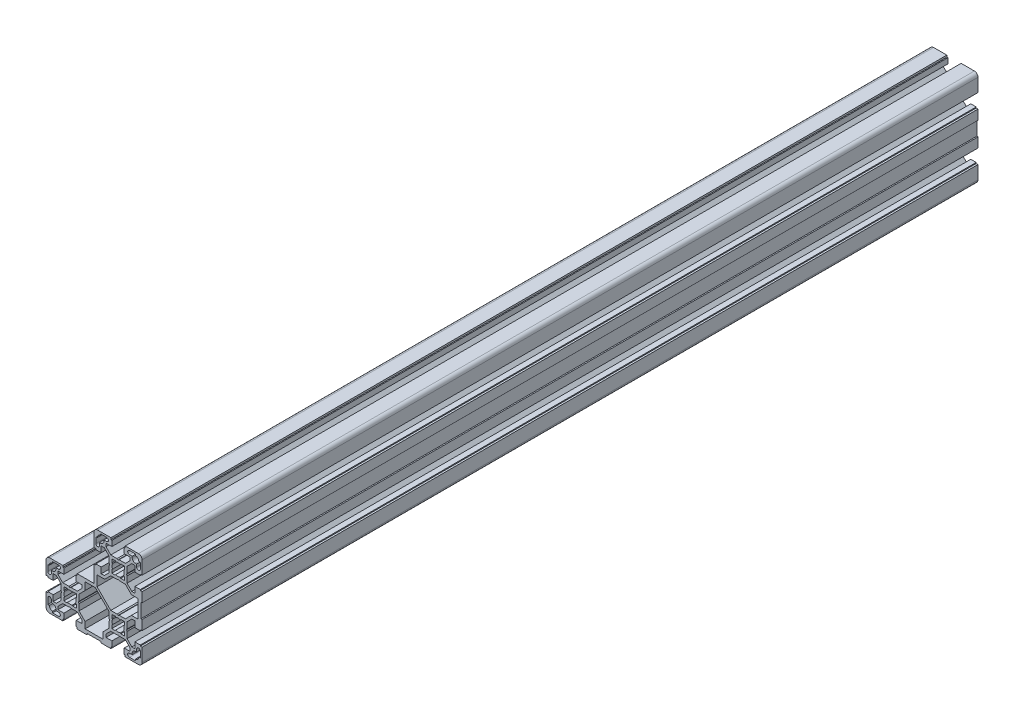
SolidWorks part; units mm, degrees
material "3.1355 (EN-AW 2024)"
ref_plane "Спереди" through (0, 0, 0) normal (0, 0, 1) x (1, 0, 0)
ref_plane "Сверху" through (0, 0, 0) normal (0, 1, 0) x (1, 0, 0)
ref_plane "Справа" through (0, 0, 0) normal (1, 0, 0) x (0, 0, -1)
sketch "Model" plane through (0, 0, 0) normal (0, 0, 1) x (1, 0, 0)
  point P0 (0, 1)
  line B0 (-35.5, 31.7499) -> (-35.5, 29.4999)
  line B1 (-38.5, 29.4999) -> (-38.5, 34.4999)
  line B2 (-38.5, 34.4999) -> (-37.25, 34.4999)
  line B3 (-34.5, 37.2499) -> (-34.5, 38.4999)
  line B4 (-34.5, 38.4999) -> (-29.5, 38.4999)
  line B5 (-29.5, 35.4999) -> (-31.75, 35.4999)
  line B6 (-31.75, 35.4999) -> (-31.75, 34.5077)
  line B7 (-34.5, 31.7499) -> (-35.5, 31.7499)
  line B8 (1.0858, 37.5) -> (12.5001, 26.0857)
  line B9 (12.5001, 26.0857) -> (12.5001, 20.866)
  line B10 (12.5001, 20.866) -> (13.0001, 20)
  line B11 (13.0001, 20) -> (12.5001, 19.1339)
  line B12 (12.5001, 19.1339) -> (12.5001, 13.9142)
  line B13 (12.5001, 13.9142) -> (7.4501, 8.8642)
  line B14 (7.4501, 8.8642) -> (7.4501, 3.5)
  line B15 (7.4501, 3.5) -> (-7.4501, 3.5)
  line B16 (-7.4501, 3.5) -> (-7.4501, 8.8642)
  line B17 (-7.4501, 8.8642) -> (-12.5001, 13.9142)
  line B18 (-12.5001, 13.9142) -> (-12.5001, 19.1339)
  line B19 (-12.5001, 19.1339) -> (-13.0001, 20)
  line B20 (-13.0001, 20) -> (-12.5001, 20.866)
  line B21 (-12.5001, 20.866) -> (-12.5001, 26.0857)
  line B22 (-12.5001, 26.0857) -> (-7.4501, 31.1357)
  line B23 (-7.4501, 31.1357) -> (-7.4501, 37.5)
  line B24 (-7.4501, 37.5) -> (1.0858, 37.5)
  line B25 (25.2, 14.8) -> (22.2603, 14.8)
  line B26 (22.2603, 14.8) -> (21.9932, 15.4144)
  line B27 (18.0068, 15.4144) -> (17.7398, 14.8)
  line B28 (17.7398, 14.8) -> (14.8001, 14.8)
  line B29 (14.8001, 14.8) -> (14.8001, 17.7397)
  line B30 (14.8001, 17.7397) -> (15.4145, 18.0068)
  line B31 (15.4145, 21.9932) -> (14.8001, 22.2602)
  line B32 (14.8001, 22.2602) -> (14.8001, 25.1999)
  line B33 (14.8001, 25.1999) -> (17.7398, 25.1999)
  line B34 (17.7398, 25.1999) -> (18.0068, 24.5855)
  line B35 (21.9932, 24.5855) -> (22.2603, 25.1999)
  line B36 (22.2603, 25.1999) -> (25.2, 25.1999)
  line B37 (25.2, 25.1999) -> (25.2, 22.2602)
  line B38 (25.2, 22.2602) -> (24.5856, 21.9932)
  line B39 (24.5856, 18.0068) -> (25.2, 17.7397)
  line B40 (25.2, 17.7397) -> (25.2, 14.8)
  line B41 (10.5001, 75.5) -> (8.2501, 75.5)
  line B42 (8.2501, 75.5) -> (8.2501, 74.5)
  line B43 (5.4923, 71.75) -> (4.5001, 71.75)
  line B44 (4.5001, 71.75) -> (4.5001, 69.5)
  line B45 (1.5001, 69.5) -> (1.5001, 74.5)
  line B46 (1.5001, 74.5) -> (2.7501, 74.5)
  line B47 (5.5001, 77.25) -> (5.5001, 78.5)
  line B48 (5.5001, 78.5) -> (10.5001, 78.5)
  line B49 (25.2, 65.2) -> (25.2, 62.2603)
  line B50 (25.2, 62.2603) -> (24.5856, 61.9932)
  line B51 (24.5856, 58.0068) -> (25.2, 57.7398)
  line B52 (25.2, 57.7398) -> (25.2, 54.8001)
  line B53 (25.2, 54.8001) -> (22.2603, 54.8001)
  line B54 (22.2603, 54.8001) -> (21.9932, 55.4145)
  line B55 (18.0068, 55.4145) -> (17.7398, 54.8001)
  line B56 (17.7398, 54.8001) -> (14.8001, 54.8001)
  line B57 (14.8001, 54.8001) -> (14.8001, 57.7398)
  line B58 (14.8001, 57.7398) -> (15.4145, 58.0068)
  line B59 (15.4145, 61.9932) -> (14.8001, 62.2603)
  line B60 (14.8001, 62.2603) -> (14.8001, 65.2)
  line B61 (14.8001, 65.2) -> (17.7398, 65.2)
  line B62 (17.7398, 65.2) -> (18.0068, 64.5856)
  line B63 (21.9932, 64.5856) -> (22.2603, 65.2)
  line B64 (22.2603, 65.2) -> (25.2, 65.2)
  line B65 (2.5, 38.9142) -> (2.5, 47.4501)
  line B66 (2.5, 47.4501) -> (8.8643, 47.4501)
  line B67 (8.8643, 47.4501) -> (13.9143, 52.5001)
  line B68 (13.9143, 52.5001) -> (19.134, 52.5001)
  line B69 (19.134, 52.5001) -> (20, 53.0001)
  line B70 (20, 53.0001) -> (20.8661, 52.5001)
  line B71 (20.8661, 52.5001) -> (26.0858, 52.5001)
  line B72 (26.0858, 52.5001) -> (31.1358, 47.4501)
  line B73 (31.1358, 47.4501) -> (36.5, 47.4501)
  line B74 (36.5, 47.4501) -> (36.5, 32.5499)
  line B75 (36.5, 32.5499) -> (31.1358, 32.5499)
  line B76 (31.1358, 32.5499) -> (26.0858, 27.4999)
  line B77 (26.0858, 27.4999) -> (20.8661, 27.4999)
  line B78 (20.8661, 27.4999) -> (20, 26.9999)
  line B79 (20, 26.9999) -> (19.134, 27.4999)
  line B80 (19.134, 27.4999) -> (13.9143, 27.4999)
  line B81 (13.9143, 27.4999) -> (2.5, 38.9142)
  line B82 (31.75, 75.5) -> (29.5, 75.5)
  line B83 (29.5, 78.5) -> (34.5, 78.5)
  line B84 (34.5, 78.5) -> (34.5, 77.25)
  line B85 (37.25, 74.5) -> (38.5, 74.5)
  line B86 (38.5, 74.5) -> (38.5, 69.5)
  line B87 (35.5, 69.5) -> (35.5, 71.75)
  line B88 (35.5, 71.75) -> (34.5078, 71.75)
  line B89 (31.75, 74.5) -> (31.75, 75.5)
  line B90 (-22.2603, 14.8) -> (-25.2, 14.8)
  line B91 (-25.2, 14.8) -> (-25.2, 17.7397)
  line B92 (-25.2, 17.7397) -> (-24.5856, 18.0068)
  line B93 (-24.5856, 21.9932) -> (-25.2, 22.2602)
  line B94 (-25.2, 22.2602) -> (-25.2, 25.1999)
  line B95 (-25.2, 25.1999) -> (-22.2603, 25.1999)
  line B96 (-22.2603, 25.1999) -> (-21.9932, 24.5855)
  line B97 (-18.0068, 24.5855) -> (-17.7398, 25.1999)
  line B98 (-17.7398, 25.1999) -> (-14.8001, 25.1999)
  line B99 (-14.8001, 25.1999) -> (-14.8001, 22.2602)
  line B100 (-14.8001, 22.2602) -> (-15.4145, 21.9932)
  line B101 (-15.4145, 18.0068) -> (-14.8001, 17.7397)
  line B102 (-14.8001, 17.7397) -> (-14.8001, 14.8)
  line B103 (-14.8001, 14.8) -> (-17.7398, 14.8)
  line B104 (-17.7398, 14.8) -> (-18.0068, 15.4144)
  line B105 (-21.9932, 15.4144) -> (-22.2603, 14.8)
  line B106 (-35.5, 10.5) -> (-35.5, 8.25)
  line B107 (-35.5, 8.25) -> (-34.5, 8.25)
  line B108 (-31.75, 5.4922) -> (-31.75, 4.5)
  line B109 (-31.75, 4.5) -> (-29.5, 4.5)
  line B110 (-29.5, 1.5) -> (-34.5, 1.5)
  line B111 (-34.5, 1.5) -> (-34.5, 2.75)
  line B112 (-37.25, 5.5) -> (-38.5, 5.5)
  line B113 (-38.5, 5.5) -> (-38.5, 10.5)
  line B114 (35.5, 8.25) -> (35.5, 10.5)
  line B115 (38.5, 10.5) -> (38.5, 5.5)
  line B116 (38.5, 5.5) -> (37.25, 5.5)
  line B117 (34.5, 2.75) -> (34.5, 1.5)
  line B118 (34.5, 1.5) -> (29.5, 1.5)
  line B119 (29.5, 4.5) -> (31.75, 4.5)
  line B120 (31.75, 4.5) -> (31.75, 5.4922)
  line B121 (34.5, 8.25) -> (35.5, 8.25)
  line B122 (34, 30.0499) -> (34, 25.15)
  line B123 (34, 25.15) -> (38.5, 25.15)
  line B124 (38.5, 25.15) -> (38.5, 25.95)
  line B125 (38.5, 25.95) -> (40, 25.95)
  line B126 (40, 25.95) -> (40, 33.9999)
  line B127 (40, 33.9999) -> (39, 33.9999)
  line B128 (39, 33.9999) -> (39, 46.0001)
  line B129 (39, 46.0001) -> (40, 46.0001)
  line B130 (40, 46.0001) -> (40, 54.05)
  line B131 (40, 54.05) -> (38.5, 54.05)
  line B132 (38.5, 54.05) -> (38.5, 54.85)
  line B133 (38.5, 54.85) -> (34, 54.85)
  line B134 (34, 54.85) -> (34, 49.9501)
  line B135 (34, 49.9501) -> (31.4642, 49.9501)
  line B136 (31.4642, 49.9501) -> (27.5, 53.9143)
  line B137 (27.5, 53.9143) -> (27.5, 59.134)
  line B138 (27.5, 59.134) -> (27, 60)
  line B139 (27, 60) -> (27.5, 60.8661)
  line B140 (27.5, 60.8661) -> (27.5, 66.0858)
  line B141 (27.5, 66.0858) -> (31.4642, 70.05)
  line B142 (31.4642, 70.05) -> (34, 70.05)
  line B143 (34, 70.05) -> (34, 65.15)
  line B144 (34, 65.15) -> (38.5, 65.15)
  line B145 (38.5, 65.15) -> (38.5, 65.95)
  line B146 (38.5, 65.95) -> (40, 65.95)
  line B147 (40, 65.95) -> (40, 77)
  line B148 (37, 80) -> (25.95, 80)
  line B149 (25.95, 80) -> (25.95, 78.5)
  line B150 (25.95, 78.5) -> (25.15, 78.5)
  line B151 (25.15, 78.5) -> (25.15, 74)
  line B152 (25.15, 74) -> (30.05, 74)
  line B153 (30.05, 74) -> (30.05, 71.4642)
  line B154 (30.05, 71.4642) -> (26.0858, 67.5)
  line B155 (26.0858, 67.5) -> (20.8661, 67.5)
  line B156 (20.8661, 67.5) -> (20, 67)
  line B157 (20, 67) -> (19.134, 67.5)
  line B158 (19.134, 67.5) -> (13.9143, 67.5)
  line B159 (13.9143, 67.5) -> (9.9501, 71.4642)
  line B160 (9.9501, 71.4642) -> (9.9501, 74)
  line B161 (9.9501, 74) -> (14.85, 74)
  line B162 (14.85, 74) -> (14.85, 78.5)
  line B163 (14.85, 78.5) -> (14.05, 78.5)
  line B164 (14.05, 78.5) -> (14.05, 80)
  line B165 (14.05, 80) -> (3.0001, 80)
  line B166 (0.0001, 77) -> (0.0001, 65.95)
  line B167 (0.0001, 65.95) -> (1.5001, 65.95)
  line B168 (1.5001, 65.95) -> (1.5001, 65.15)
  line B169 (1.5001, 65.15) -> (6.0001, 65.15)
  line B170 (6.0001, 65.15) -> (6.0001, 70.05)
  line B171 (6.0001, 70.05) -> (8.5358, 70.05)
  line B172 (8.5358, 70.05) -> (12.5001, 66.0858)
  line B173 (12.5001, 66.0858) -> (12.5001, 60.8661)
  line B174 (12.5001, 60.8661) -> (13.0001, 60)
  line B175 (13.0001, 60) -> (12.5001, 59.134)
  line B176 (12.5001, 59.134) -> (12.5001, 53.9143)
  line B177 (12.5001, 53.9143) -> (8.5358, 49.9501)
  line B178 (8.5358, 49.9501) -> (6.0001, 49.9501)
  line B179 (6.0001, 49.9501) -> (6.0001, 54.85)
  line B180 (6.0001, 54.85) -> (1.5001, 54.85)
  line B181 (1.5001, 54.85) -> (1.5001, 54.05)
  line B182 (1.5001, 54.05) -> (0.0001, 54.05)
  line B183 (0.0001, 54.05) -> (0.0001, 40.55)
  line B184 (0.0001, 40.55) -> (0.188, 40.0337)
  line B185 (0.188, 40.0337) -> (-0.0337, 39.812)
  line B186 (-0.0337, 39.812) -> (-0.55, 39.9999)
  line B187 (-0.55, 39.9999) -> (-14.05, 39.9999)
  line B188 (-14.05, 39.9999) -> (-14.05, 38.4999)
  line B189 (-14.05, 38.4999) -> (-14.85, 38.4999)
  line B190 (-14.85, 38.4999) -> (-14.85, 33.9999)
  line B191 (-14.85, 33.9999) -> (-9.9501, 33.9999)
  line B192 (-9.9501, 33.9999) -> (-9.9501, 31.4642)
  line B193 (-9.9501, 31.4642) -> (-13.9143, 27.4999)
  line B194 (-13.9143, 27.4999) -> (-19.134, 27.4999)
  line B195 (-19.134, 27.4999) -> (-20, 26.9999)
  line B196 (-20, 26.9999) -> (-20.8661, 27.4999)
  line B197 (-20.8661, 27.4999) -> (-26.0858, 27.4999)
  line B198 (-26.0858, 27.4999) -> (-30.05, 31.4642)
  line B199 (-30.05, 31.4642) -> (-30.05, 33.9999)
  line B200 (-30.05, 33.9999) -> (-25.15, 33.9999)
  line B201 (-25.15, 33.9999) -> (-25.15, 38.4999)
  line B202 (-25.15, 38.4999) -> (-25.95, 38.4999)
  line B203 (-25.95, 38.4999) -> (-25.95, 39.9999)
  line B204 (-25.95, 39.9999) -> (-37, 39.9999)
  line B205 (-40, 36.9999) -> (-40, 25.95)
  line B206 (-40, 25.95) -> (-38.5, 25.95)
  line B207 (-38.5, 25.95) -> (-38.5, 25.15)
  line B208 (-38.5, 25.15) -> (-34, 25.15)
  line B209 (-34, 25.15) -> (-34, 30.0499)
  line B210 (-34, 30.0499) -> (-31.4642, 30.0499)
  line B211 (-31.4642, 30.0499) -> (-27.5, 26.0857)
  line B212 (-27.5, 26.0857) -> (-27.5, 20.866)
  line B213 (-27.5, 20.866) -> (-27, 20)
  line B214 (-27, 20) -> (-27.5, 19.1339)
  line B215 (-27.5, 19.1339) -> (-27.5, 13.9142)
  line B216 (-27.5, 13.9142) -> (-31.4642, 9.95)
  line B217 (-31.4642, 9.95) -> (-34, 9.95)
  line B218 (-34, 9.95) -> (-34, 14.85)
  line B219 (-34, 14.85) -> (-38.5, 14.85)
  line B220 (-38.5, 14.85) -> (-38.5, 14.05)
  line B221 (-38.5, 14.05) -> (-40, 14.05)
  line B222 (-40, 14.05) -> (-40, 3)
  line B223 (-37, 0) -> (-25.95, 0)
  line B224 (-25.95, 0) -> (-25.95, 1.5)
  line B225 (-25.95, 1.5) -> (-25.15, 1.5)
  line B226 (-25.15, 1.5) -> (-25.15, 6)
  line B227 (-25.15, 6) -> (-30.05, 6)
  line B228 (-30.05, 6) -> (-30.05, 8.5358)
  line B229 (-30.05, 8.5358) -> (-26.0858, 12.5)
  line B230 (-26.0858, 12.5) -> (-20.8661, 12.5)
  line B231 (-20.8661, 12.5) -> (-20, 13)
  line B232 (-20, 13) -> (-19.134, 12.5)
  line B233 (-19.134, 12.5) -> (-13.9143, 12.5)
  line B234 (-13.9143, 12.5) -> (-9.9501, 8.5358)
  line B235 (-9.9501, 8.5358) -> (-9.9501, 6)
  line B236 (-9.9501, 6) -> (-14.85, 6)
  line B237 (-14.85, 6) -> (-14.85, 1.5)
  line B238 (-14.85, 1.5) -> (-14.05, 1.5)
  line B239 (-14.05, 1.5) -> (-14.05, 0)
  line B240 (-14.05, 0) -> (-6.0001, 0)
  line B241 (-6.0001, 0) -> (-6.0001, 1)
  line B242 (-6.0001, 1) -> (6.0001, 1)
  line B243 (6.0001, 1) -> (6.0001, 0)
  line B244 (6.0001, 0) -> (14.05, 0)
  line B245 (14.05, 0) -> (14.05, 1.5)
  line B246 (14.05, 1.5) -> (14.85, 1.5)
  line B247 (14.85, 1.5) -> (14.85, 6)
  line B248 (14.85, 6) -> (9.9501, 6)
  line B249 (9.9501, 6) -> (9.9501, 8.5358)
  line B250 (9.9501, 8.5358) -> (13.9143, 12.5)
  line B251 (13.9143, 12.5) -> (19.134, 12.5)
  line B252 (19.134, 12.5) -> (20, 13)
  line B253 (20, 13) -> (20.8661, 12.5)
  line B254 (20.8661, 12.5) -> (26.0858, 12.5)
  line B255 (26.0858, 12.5) -> (30.05, 8.5358)
  line B256 (30.05, 8.5358) -> (30.05, 6)
  line B257 (30.05, 6) -> (25.15, 6)
  line B258 (25.15, 6) -> (25.15, 1.5)
  line B259 (25.15, 1.5) -> (25.95, 1.5)
  line B260 (25.95, 1.5) -> (25.95, 0)
  line B261 (25.95, 0) -> (37, 0)
  line B262 (40, 3) -> (40, 14.05)
  line B263 (40, 14.05) -> (38.5, 14.05)
  line B264 (38.5, 14.05) -> (38.5, 14.85)
  line B265 (38.5, 14.85) -> (34, 14.85)
  line B266 (34, 14.85) -> (34, 9.95)
  line B267 (34, 9.95) -> (31.4642, 9.95)
  line B268 (31.4642, 9.95) -> (27.5, 13.9142)
  line B269 (27.5, 13.9142) -> (27.5, 19.1339)
  line B270 (27.5, 19.1339) -> (27, 20)
  line B271 (27, 20) -> (27.5, 20.866)
  line B272 (27.5, 20.866) -> (27.5, 26.0857)
  line B273 (27.5, 26.0857) -> (31.4642, 30.0499)
  line B274 (31.4642, 30.0499) -> (34, 30.0499)
  arc B275 (-38.5, 29.4999) -> (-35.5, 29.4999) centre (-37, 29.4999) ccw
  arc B276 (-34.5, 37.2499) -> (-37.25, 34.4999) centre (-34.5, 34.4999) ccw
  arc B277 (-29.5, 35.4999) -> (-29.5, 38.4999) centre (-29.5, 36.9999) ccw
  arc B278 (-34.5, 31.7499) -> (-31.75, 34.5077) centre (-34.5, 34.4999) ccw
  arc B279 (18.0068, 15.4144) -> (21.9932, 15.4144) centre (20, 20) ccw
  arc B280 (15.4145, 21.9932) -> (15.4145, 18.0068) centre (20, 20) ccw
  arc B281 (21.9932, 24.5855) -> (18.0068, 24.5855) centre (20, 20) ccw
  arc B282 (24.5856, 18.0068) -> (24.5856, 21.9932) centre (20, 20) ccw
  arc B283 (5.4923, 71.75) -> (8.2501, 74.5) centre (5.5001, 74.5) ccw
  arc B284 (1.5001, 69.5) -> (4.5001, 69.5) centre (3.0001, 69.5) ccw
  arc B285 (5.5001, 77.25) -> (2.7501, 74.5) centre (5.5001, 74.5) ccw
  arc B286 (10.5001, 75.5) -> (10.5001, 78.5) centre (10.5001, 77) ccw
  arc B287 (24.5856, 58.0068) -> (24.5856, 61.9932) centre (20, 60) ccw
  arc B288 (18.0068, 55.4145) -> (21.9932, 55.4145) centre (20, 60) ccw
  arc B289 (15.4145, 61.9932) -> (15.4145, 58.0068) centre (20, 60) ccw
  arc B290 (21.9932, 64.5856) -> (18.0068, 64.5856) centre (20, 60) ccw
  arc B291 (29.5, 78.5) -> (29.5, 75.5) centre (29.5, 77) ccw
  arc B292 (37.25, 74.5) -> (34.5, 77.25) centre (34.5, 74.5) ccw
  arc B293 (35.5, 69.5) -> (38.5, 69.5) centre (37, 69.5) ccw
  arc B294 (31.75, 74.5) -> (34.5078, 71.75) centre (34.5, 74.5) ccw
  arc B295 (-24.5856, 21.9932) -> (-24.5856, 18.0068) centre (-20, 20) ccw
  arc B296 (-18.0068, 24.5855) -> (-21.9932, 24.5855) centre (-20, 20) ccw
  arc B297 (-15.4145, 18.0068) -> (-15.4145, 21.9932) centre (-20, 20) ccw
  arc B298 (-21.9932, 15.4144) -> (-18.0068, 15.4144) centre (-20, 20) ccw
  arc B299 (-31.75, 5.4922) -> (-34.5, 8.25) centre (-34.5, 5.5) ccw
  arc B300 (-29.5, 1.5) -> (-29.5, 4.5) centre (-29.5, 3) ccw
  arc B301 (-37.25, 5.5) -> (-34.5, 2.75) centre (-34.5, 5.5) ccw
  arc B302 (-35.5, 10.5) -> (-38.5, 10.5) centre (-37, 10.5) ccw
  arc B303 (38.5, 10.5) -> (35.5, 10.5) centre (37, 10.5) ccw
  arc B304 (34.5, 2.75) -> (37.25, 5.5) centre (34.5, 5.5) ccw
  arc B305 (29.5, 4.5) -> (29.5, 1.5) centre (29.5, 3) ccw
  arc B306 (34.5, 8.25) -> (31.75, 5.4922) centre (34.5, 5.5) ccw
  arc B307 (40, 77) -> (37, 80) centre (37, 77) ccw
  arc B308 (3.0001, 80) -> (0.0001, 77) centre (3.0001, 77) ccw
  arc B309 (-37, 39.9999) -> (-40, 36.9999) centre (-37, 36.9999) ccw
  arc B310 (-40, 3) -> (-37, 0) centre (-37, 3) ccw
  arc B311 (37, 0) -> (40, 3) centre (37, 3) ccw
sketch_block_instance "Блок1-1"
sketch_block "Блок1"
extrude "База" add sketch "Model" against normal mid plane 696
